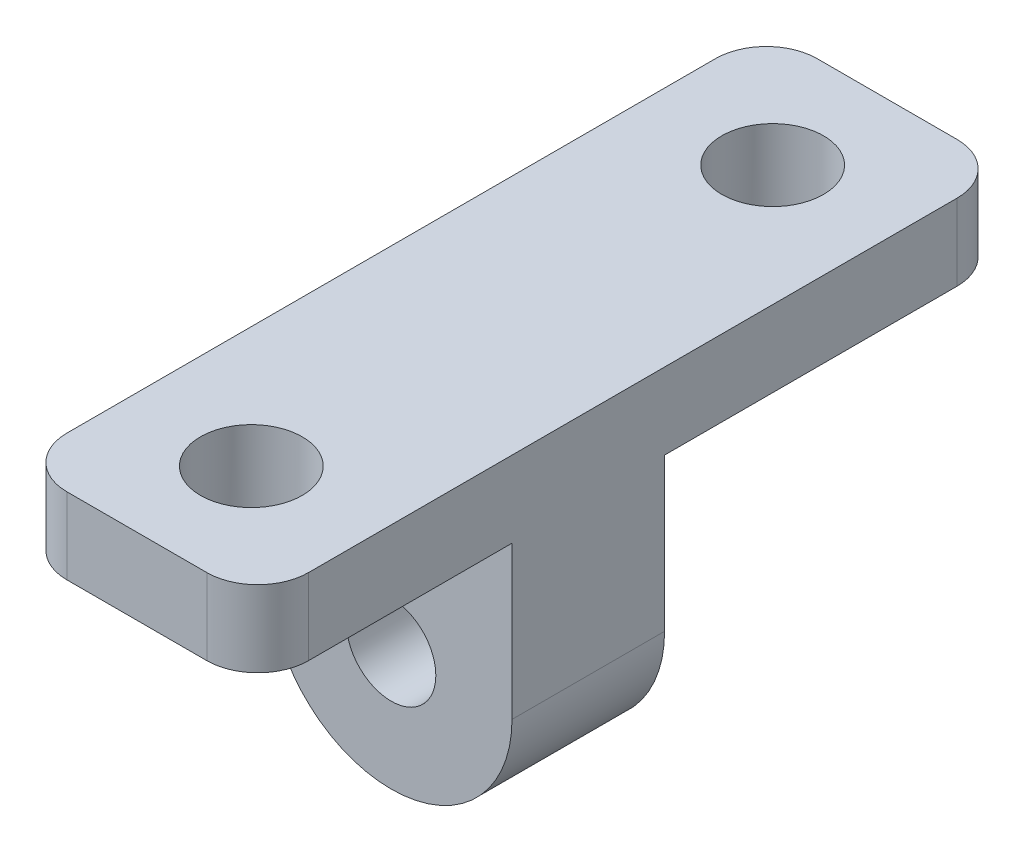
SolidWorks part; units mm, degrees
ref_plane "Front Plane" through (0, 0, 0) normal (0, 0, 1) x (1, 0, 0)
ref_plane "Top Plane" through (0, 0, 0) normal (0, 1, 0) x (1, 0, 0)
ref_plane "Right Plane" through (0, 0, 0) normal (1, 0, 0) x (0, 0, -1)
sketch "Sketch2" plane through (0, 0, 0) normal (0, 0, 1) x (1, 0, 0)
  line L0 (-4.75, 0) -> (-4.75, 6)
  line L1 (-4.75, 6) -> (4.75, 6)
  line L2 (4.75, 6) -> (4.75, 0)
  circle A0 centre (0, 0) radius 4.75
  circle A1 centre (0, 0) radius 1.755
  dimension "D1" = 3.51
  dimension "D2" = 9.5
  dimension "D3" = 6
extrude "Boss-Extrude1" add sketch "Sketch2" along normal blind 6 contours A0 A1 | A0 L1 L0 | A0 L2 L1
sketch "Sketch3" plane through (0, 6, 0) normal (0, 1, 0) x (1, 0, 0)
  line L0 (0, -16) -> (0, -6) construction
  line L1 (-4.75, 13.5) -> (4.75, 13.5)
  line L2 (-4.75, 13.5) -> (-4.75, -16)
  line L3 (-4.75, -16) -> (4.75, -16)
  line L4 (4.75, 13.5) -> (4.75, -16)
  line L5 (-4.75, -6) -> (4.75, -6) construction
  line L6 (0, 13.5) -> (0, 0) construction
  line L7 (-4.75, 0) -> (4.75, 0) construction
  line L8 (-4.75, -6) -> (-4.75, 0) construction
  dimension "D1" = 13.5
  dimension "D2" = 10
extrude "Boss-Extrude2" add sketch "Sketch3" along normal blind 3 contours L2 L3 L4 L1
sketch "Sketch4" plane through (0, 9, 0) normal (0, 1, 0) x (1, 0, 0)
  line L0 (0, -16) -> (0, 13.5) construction
  line L1 (-4.75, -16) -> (4.75, -16) construction
  line L2 (-4.75, 13.5) -> (4.75, 13.5) construction
  circle A0 centre (0, -11.5) radius 2
  circle A1 centre (0, 9) radius 2
  point P10 (0, 0)
  point P11 (0, 0)
  dimension "D3" = 4
  dimension "D1" = 4.5
  dimension "D2" = 4.5
extrude "Cut-Extrude1" cut sketch "Sketch4" against normal through all
fillet "Fillet1" radius 2 4 edges at (4.75, 7.5, -13.5) (-4.75, 7.5, -13.5) (-4.75, 7.5, 16) (4.75, 7.5, 16)
